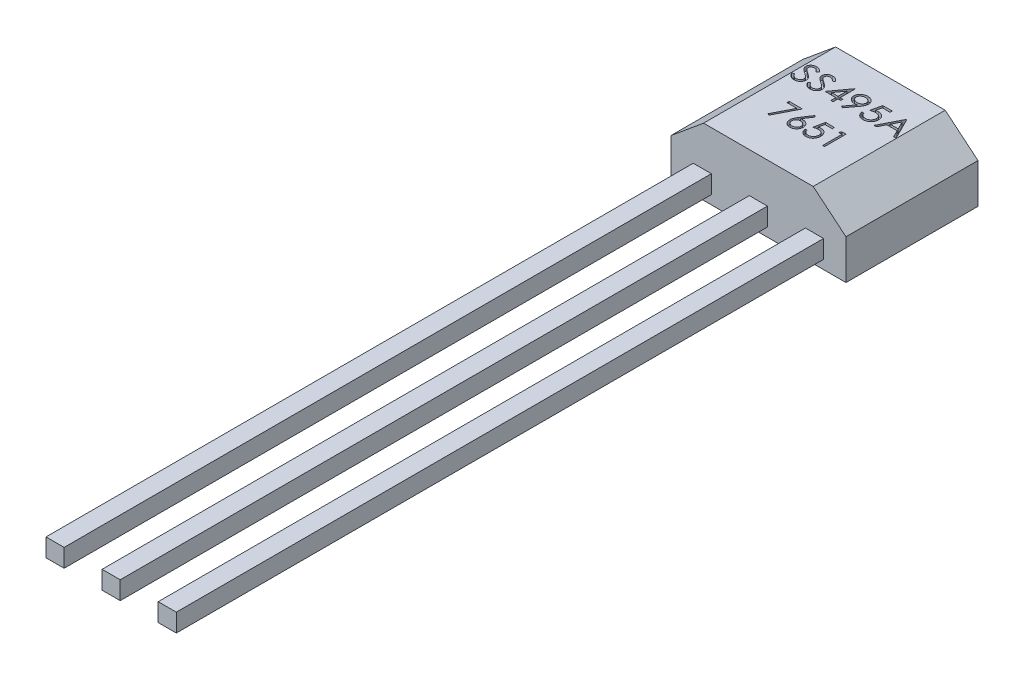
SolidWorks part; units mm, degrees
ref_plane "Front Plane" through (0, 0, 0) normal (0, 0, 1) x (1, 0, 0)
ref_plane "Top Plane" through (0, 0, 0) normal (0, 1, 0) x (1, 0, 0)
ref_plane "Right Plane" through (0, 0, 0) normal (1, 0, 0) x (0, 0, -1)
sketch "Sketch1" plane through (0, 0, 0) normal (0, 0, 1) x (1, 0, 0)
  line L0 (0, 3.4797) -> (0, -3.0494) construction
  line L1 (-4.0065, 0) -> (3.8135, 0) construction
  line L2 (-2.03, 0.145) -> (-2.03, -0.775)
  line L3 (-2.03, -0.775) -> (2.03, -0.775)
  line L5 (1.27, 0.775) -> (-1.27, 0.775)
  line L6 (-1.27, 0.775) -> (-2.03, 0.145)
  line L7 (1.27, 0.775) -> (2.03, 0.145)
  line L8 (2.03, 0.145) -> (2.03, -0.775)
  dimension "D1" = 0.92
  dimension "D2" = 1.55
  dimension "D3" = 2.54
  dimension "D4" = 4.06
  dimension "D5" = 0.9872
extrude "Boss-Extrude1" add sketch "Sketch1" along normal mid plane 3.06
sketch "Sketch2" plane through (0, 0, 1.53) normal (0, 0, 1) x (1, 0, 0)
  line L0 (0, 1.2899) -> (0, -1.431) construction
  line L1 (-1.3, -0.3594) -> (1.8227, -0.3594) construction
  line L2 (-1.51, -0.1494) -> (-1.09, -0.1494)
  line L3 (-1.51, -0.1494) -> (-1.51, -0.5694)
  line L4 (-1.51, -0.5694) -> (-1.09, -0.5694)
  line L5 (-1.09, -0.1494) -> (-1.09, -0.5694)
  line L6 (-1.51, -0.1494) -> (-1.09, -0.5694) construction
  line L7 (-1.51, -0.5694) -> (-1.09, -0.1494) construction
  line L8 (1.51, -0.5694) -> (1.09, -0.5694)
  line L9 (1.09, -0.1494) -> (1.09, -0.5694)
  line L10 (1.51, -0.1494) -> (1.09, -0.1494)
  line L11 (1.51, -0.1494) -> (1.51, -0.5694)
  line L13 (-0.21, -0.1494) -> (0.21, -0.1494)
  line L14 (-0.21, -0.1494) -> (-0.21, -0.5694)
  line L15 (-0.21, -0.5694) -> (0.21, -0.5694)
  line L16 (0.21, -0.1494) -> (0.21, -0.5694)
  line L17 (-0.21, -0.1494) -> (0.21, -0.5694) construction
  line L18 (-0.21, -0.5694) -> (0.21, -0.1494) construction
  point P0 (-1.3, -0.3594)
  point P14 (0, -0.3594)
  dimension "D1" = 0.42
  dimension "D2" = 0.42
  dimension "D3" = 2.6
  dimension "D4" = 0.42
  dimension "D5" = 0.42
extrude "Boss-Extrude2" add sketch "Sketch2" along normal blind 15
sketch "Sketch3" plane through (0, 0.775, 0) normal (0, 1, 0) x (1, 0, 0)
  line L0 (-1.27, 0.4) -> (1.27, 0.4) construction
  line L1 (-1.27, -1.53) -> (-1.27, 1.53) construction
  line L2 (1.27, -1.53) -> (1.27, 1.53) construction
  line L3 (-1.27, 0) -> (1.27, 0) construction
  line L4 (-1.27, -0.6) -> (1.27, -0.6) construction
  text T0 "SS495A" font "Century Gothic" height 0.5
  text T1 "7651" font "Century Gothic" height 0.5
  dimension "D1" = 0.4
  dimension "D2" = 0.6
extrude "Cut-Extrude1" cut sketch "Sketch3" against normal blind 0.1
